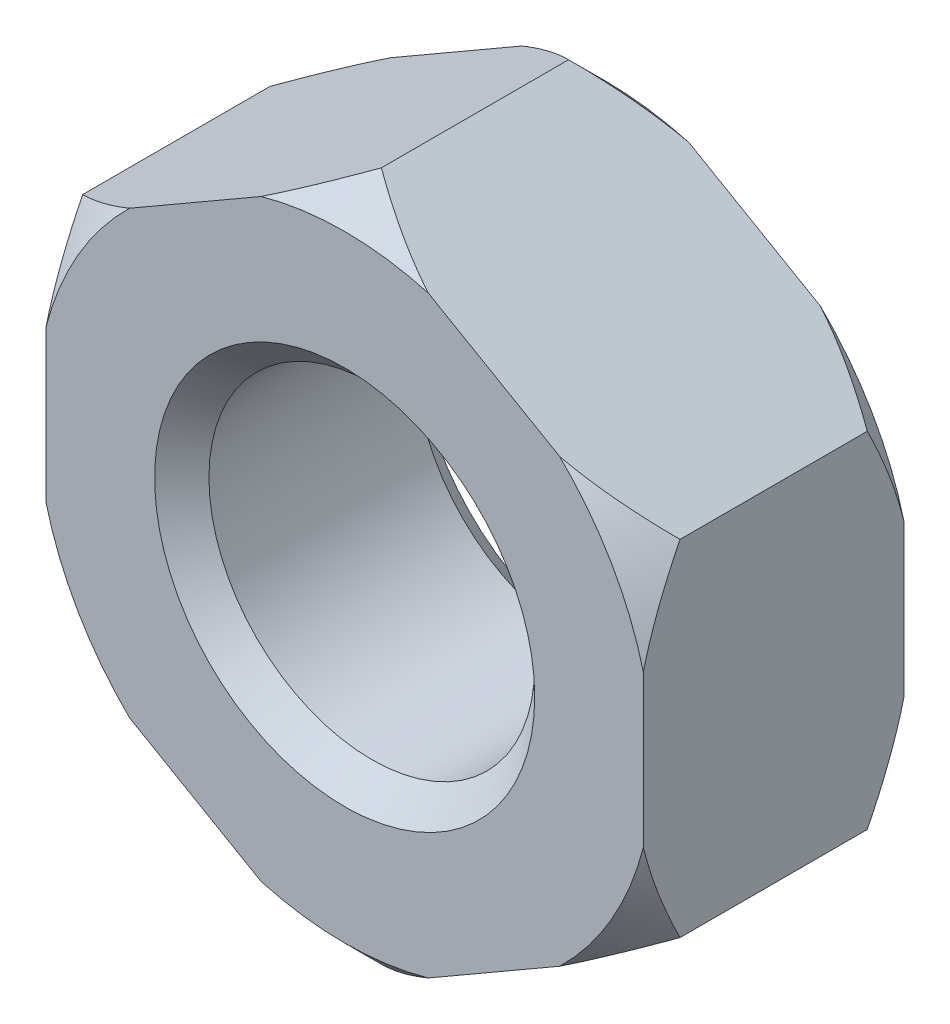
SolidWorks part; units mm, degrees
ref_plane "Спереди" through (0, 0, 0) normal (0, 0, 1) x (1, 0, 0)
ref_plane "Сверху" through (0, 0, 0) normal (0, 1, 0) x (1, 0, 0)
ref_plane "Справа" through (0, 0, 0) normal (1, 0, 0) x (0, 0, -1)
sketch "Эскиз1" plane through (0, 0, 0) normal (0, 0, 1) x (1, 0, 0)
  line L0 (0, 3.7738) -> (0, -4.1898) construction
  line L1 (-3.4469, 0) -> (3.2389, 0) construction
  line L3 (0, 3.1754) -> (-2.75, 1.5877)
  line L4 (-2.75, 1.5877) -> (-2.75, -1.5877)
  line L5 (-2.75, -1.5877) -> (0, -3.1754)
  line L6 (0, -3.1754) -> (2.75, -1.5877)
  line L7 (2.75, -1.5877) -> (2.75, 1.5877)
  line L8 (2.75, 1.5877) -> (0, 3.1754)
  circle A0 centre (0, 0) radius 2.75 construction
extrude "Вытянуть1" add sketch "Эскиз1" along normal blind 2.4
sketch "Эскиз2" plane through (0, 0, 0) normal (0, 0, -1) x (-1, 0, 0)
  circle A0 centre (0, 0) radius 1.5
ref_axis "Ось4" through (0, 0, 2.6338) along (0, 0, -1)
sketch "Эскиз15" plane through (0, 0, 0) normal (1, 0, 0) x (0, 0, -1)
  line L0 (-2.4, 3.1754) -> (-2.4, 2.8374)
  line L1 (-2.4, 1.5877) -> (-2.4, 3.1754) construction
  line L2 (-2.4, 2.8374) -> (-2.062, 3.1754)
  line L3 (-2.4, 3.1754) -> (0, 3.1754) construction
  line L4 (-2.062, 3.1754) -> (-2.4, 3.1754)
  line L5 (-0.338, 3.1754) -> (0, 3.1754)
  line L6 (0, 3.1754) -> (0, 2.8374)
  line L7 (0, 2.8374) -> (-0.338, 3.1754)
revolve "Вырез-Повернуть1" cut sketch "Эскиз15" angle 360 about axis through (0, 0, 2.6338) along (0, 0, -1)
ref_plane "Плоскость1" through (2.75, 0.6989, 2.4) normal (-0.2463, 0.9692, 0) x (-0.9692, -0.2463, 0)
extrude "Вырез-Вытянуть1" cut sketch "Эскиз2" against normal through all
chamfer "Фаска1" distance 0.25 angle 45 2 edges at (-1.5, 0, 0) (-1.5, 0, 2.4)
